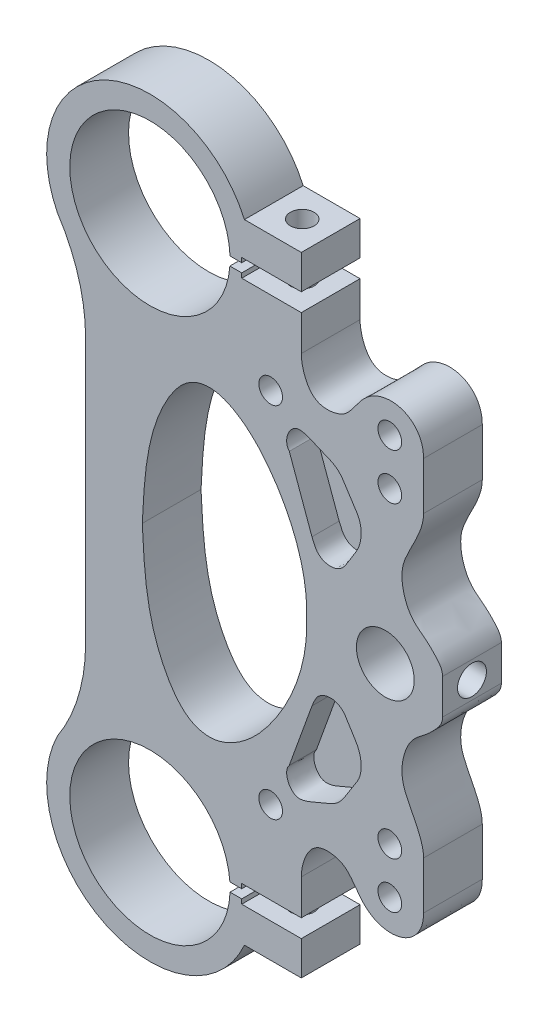
SolidWorks part; units mm, degrees
ref_plane "Piano frontale" through (0, 0, 0) normal (0, 0, 1) x (1, 0, 0)
ref_plane "Piano superiore" through (0, 0, 0) normal (0, 1, 0) x (1, 0, 0)
ref_plane "Piano destro" through (0, 0, 0) normal (1, 0, 0) x (0, 0, -1)
sketch "Schizzo1" plane through (0, 0, 0) normal (0, 0, 1) x (1, 0, 0)
  line L0 (44.652, 38.3399) -> (-8.3277, 38.3399) construction
  line L1 (10.783, 26.8988) -> (10.783, 49.781)
  line L2 (24.2823, 62.1538) -> (24.2823, 62.5538)
  line L3 (24.2823, 62.5538) -> (29.4323, 62.5538)
  line L4 (29.4323, 62.5538) -> (29.4323, 65.5038)
  line L5 (29.4323, 65.5038) -> (24.5149, 65.5038)
  line L6 (24.2823, 62.1538) -> (23.2712, 62.1538)
  line L7 (23.258, 61.3982) -> (24.2823, 61.3982)
  line L8 (24.2823, 61.3982) -> (24.2823, 60.9982)
  line L9 (24.2823, 60.9982) -> (29.4323, 60.9982)
  line L10 (29.4323, 60.9982) -> (29.4323, 57.9329)
  line L11 (40.0008, 55.359) -> (40.0008, 51.2344)
  line L12 (41.648, 39.8619) -> (41.648, 36.8178)
  line L13 (40.0008, 21.3208) -> (40.0008, 25.4454)
  line L14 (29.4323, 15.6815) -> (29.4323, 18.7468)
  line L15 (24.2823, 15.6815) -> (29.4323, 15.6815)
  line L16 (24.2823, 15.2815) -> (24.2823, 15.6815)
  line L17 (23.258, 15.2815) -> (24.2823, 15.2815)
  line L18 (24.2823, 14.5259) -> (23.2712, 14.5259)
  line L19 (29.4323, 11.1759) -> (24.5149, 11.1759)
  line L20 (29.4323, 14.1259) -> (29.4323, 11.1759)
  line L21 (24.2823, 14.1259) -> (29.4323, 14.1259)
  line L22 (24.2823, 14.5259) -> (24.2823, 14.1259)
  line L23 (28.3915, 50.0978) -> (30.3532, 44.6715) construction
  line L24 (28.3915, 26.5819) -> (30.3532, 32.0083) construction
  line L25 (37.083, 51.6399) -> (37.083, 55.6399) construction
  circle A0 centre (36.6966, 38.3399) radius 2.5
  circle A1 centre (16.3459, 61.8965) radius 6.93
  arc A2 (24.5149, 65.5038) -> (9.0355, 56.7679) centre (16.3459, 61.8965) ccw
  arc A3 (10.783, 49.781) -> (8.3437, 57.9329) centre (-4.0586, 49.781) ccw
  circle A4 centre (16.3459, 61.8965) radius 8.93 construction
  arc A5 (10.783, 26.8988) -> (8.3437, 18.7468) centre (-4.0586, 26.8988) cw
  arc A6 (24.5149, 11.1759) -> (9.0355, 19.9118) centre (16.3459, 14.7832) cw
  circle A7 centre (16.3459, 14.7832) radius 6.93
  circle A8 centre (26.783, 53.8399) radius 1.1499 construction
  circle A9 centre (37.083, 55.6399) radius 1.1192 construction
  circle A10 centre (37.083, 51.6399) radius 1.0752 construction
  circle A11 centre (26.783, 22.8399) radius 1.1499 construction
  circle A12 centre (37.083, 21.0399) radius 1.1192 construction
  circle A13 centre (37.083, 25.0399) radius 1.0752 construction
  spline S0 degree 3 poles (40.0008, 55.359) (40.0008, 55.8035) (39.8397, 56.7649) (38.7622, 58.0352) (36.9415, 58.4478) (35.0744, 57.7178) (34.1411, 56.3789) (33.2869, 55.2468) (32.1191, 54.8054) (30.8052, 54.8766) (29.7077, 56.046) (29.4323, 57.3454) (29.4323, 57.9329) knots 0 0 0 0 0.086235 0.18461 0.30636 0.425659 0.552279 0.62003 0.697314 0.787231 0.85642 1 1 1 1
  spline S1 degree 3 poles (40.0008, 51.2344) (40.0008, 50.771) (39.7217, 49.6561) (38.9038, 48.1195) (38.0379, 46.3694) (38.1748, 44.4393) (38.9027, 42.8192) (40.12, 41.9865) (41.0426, 41.1272) (41.648, 40.3961) (41.648, 39.8619) knots 0 0 0 0 0.103904 0.2667 0.404029 0.548278 0.701668 0.797389 0.884227 1 1 1 1
  spline S2 degree 3 poles (40.0008, 25.4454) (40.0008, 25.9087) (39.7217, 27.0237) (38.9038, 28.5602) (38.0379, 30.3104) (38.1748, 32.2404) (38.9027, 33.8605) (40.12, 34.6933) (41.0426, 35.5525) (41.648, 36.2836) (41.648, 36.8178) knots 0 0 0 0 0.103904 0.2667 0.404029 0.548278 0.701668 0.797389 0.884227 1 1 1 1
  spline S3 degree 3 poles (40.0008, 21.3208) (40.0008, 20.8762) (39.8397, 19.9149) (38.7622, 18.6446) (36.9415, 18.232) (35.0744, 18.9619) (34.1411, 20.3009) (33.2869, 21.4329) (32.1191, 21.8743) (30.8052, 21.8031) (29.7077, 20.6337) (29.4323, 19.3344) (29.4323, 18.7468) knots 0 0 0 0 0.086235 0.18461 0.30636 0.425659 0.552279 0.62003 0.697314 0.787231 0.85642 1 1 1 1
  spline S4 degree 3 poles (15.6826, 38.3399) (15.8621, 41.8407) (16.077, 46.4843) (19.436, 51.1792) (22.0032, 51.5591) (24.463, 50.5183) (27.0177, 47.7705) (29.3099, 43.5608) (29.9723, 40.1777) (29.8861, 38.3399) knots 0 0 0 0 0.321955 0.444159 0.483908 0.555795 0.683183 0.828712 1 1 1 1
  spline S5 degree 3 poles (15.6826, 38.3399) (15.8621, 34.839) (16.077, 30.1954) (19.436, 25.5005) (22.0032, 25.1207) (24.463, 26.1614) (27.0177, 28.9092) (29.3099, 33.119) (29.9723, 36.5021) (29.8861, 38.3399) knots 0 0 0 0 0.321955 0.444159 0.483908 0.555795 0.683183 0.828712 1 1 1 1
  spline S6 degree 3 poles (28.3915, 50.0978) (27.8594, 50.7048) (28.4692, 52.3186) (30.0286, 52.0526) (31.1131, 51.4818) (32.3557, 51.1014) (33.193, 50.1474) (33.7119, 49.1497) (34.5378, 48.0878) (34.6681, 46.8838) (34.3882, 45.7037) (33.6402, 44.7109) (33.0671, 43.5351) (32.0346, 43.17) (31.284, 43.3773) (30.8794, 43.6857) (30.6816, 43.8562) (30.3532, 44.6715) knots 0 0 0 0 0.13684 0.17515 0.257072 0.352961 0.390177 0.472943 0.54801 0.617627 0.673801 0.753613 0.832487 0.887817 0.933329 0.944548 1 1 1 1 construction
  spline S7 degree 3 poles (28.3915, 26.5819) (27.8594, 25.9749) (28.4692, 24.3611) (30.0286, 24.6271) (31.1131, 25.1979) (32.3557, 25.5784) (33.193, 26.5324) (33.7119, 27.53) (34.5378, 28.592) (34.6681, 29.7959) (34.3882, 30.9761) (33.6402, 31.9689) (33.0671, 33.1447) (32.0346, 33.5098) (31.284, 33.3025) (30.8794, 32.994) (30.6816, 32.8235) (30.3532, 32.0083) knots 0 0 0 0 0.13684 0.17515 0.257072 0.352961 0.390177 0.472943 0.54801 0.617627 0.673801 0.753613 0.832487 0.887817 0.933329 0.944548 1 1 1 1 construction
  point P72 (41.648, 38.3399)
  point P81 (10.783, 38.3399)
  dimension "D1" = 5
  dimension "D2" = 13.86
  dimension "D3" = 2.95
  dimension "D4" = 0.4
  dimension "D5" = 5.15
  dimension "D7" = 4
  dimension "D8" = 15.5
  dimension "D9" = 16
  dimension "D10" = 26.3
  dimension "D11" = 13.3
  dimension "D6" = 2
extrude "Estrusione-Estrusione1" add sketch "Schizzo1" along normal blind 5.08 contours S3 L13 S2 L12 S1 L11 S0 L10 L9 L8 L7 A1 L6 L2 L3 L4 L5 A2 A3 L1 A5 A6 L19 L20 L21 L22 L18 A7 L17 L16 L15 L14 S5 S4 A0
sketch "Schizzo2" plane through (0, 0, 5.08) normal (0, 0, 1) x (1, 0, 0)
  line L0 (28.3915, 50.0978) -> (30.3532, 44.6715) construction
  line L1 (28.3915, 26.5819) -> (30.3532, 32.0083) construction
  line L2 (28.3915, 50.0978) -> (30.3532, 44.6715)
  line L3 (28.3915, 26.5819) -> (30.3532, 32.0083)
  spline S0 degree 3 poles (1436.732, 2697.3918) (51.5713, -113.5731) (19.2159, 53.8971) (30.0286, 52.0526) (31.1131, 51.4818) (32.3557, 51.1014) (33.193, 50.1474) (33.7119, 49.1497) (34.5378, 48.0878) (34.6681, 46.8838) (34.3882, 45.7037) (33.6402, 44.7109) (33.0671, 43.5351) (32.0346, 43.17) (31.284, 43.3773) (27.8435, 46.0003) (32.4766, 46.1184) (-774.2479, 2934.6543) knots -1.525496 -1.525496 -1.525496 -1.525496 0.13684 0.17515 0.257072 0.352961 0.390177 0.472943 0.54801 0.617627 0.673801 0.753613 0.832487 0.887817 0.933329 0.944548 1.841826 1.841826 1.841826 1.841826 only from (28.3915, 50.0978) to (30.3532, 44.6715) construction
  spline S1 degree 3 poles (1436.732, -2620.712) (51.5713, 190.2528) (19.2159, 22.7827) (30.0286, 24.6271) (31.1131, 25.1979) (32.3557, 25.5784) (33.193, 26.5324) (33.7119, 27.53) (34.5378, 28.592) (34.6681, 29.7959) (34.3882, 30.9761) (33.6402, 31.9689) (33.0671, 33.1447) (32.0346, 33.5098) (31.284, 33.3025) (27.8435, 30.6795) (32.4766, 30.5613) (-774.2479, -2857.9746) knots -1.525496 -1.525496 -1.525496 -1.525496 0.13684 0.17515 0.257072 0.352961 0.390177 0.472943 0.54801 0.617627 0.673801 0.753613 0.832487 0.887817 0.933329 0.944548 1.841826 1.841826 1.841826 1.841826 only from (28.3915, 26.5819) to (30.3532, 32.0083) construction
  spline S2 degree 3 poles (28.3915, 50.0978) (27.8594, 50.7048) (28.4692, 52.3186) (30.0286, 52.0526) (31.1131, 51.4818) (32.3557, 51.1014) (33.193, 50.1474) (33.7119, 49.1497) (34.5378, 48.0878) (34.6681, 46.8838) (34.3882, 45.7037) (33.6402, 44.7109) (33.0671, 43.5351) (32.0346, 43.17) (31.284, 43.3773) (30.8794, 43.6857) (30.6816, 43.8562) (30.3532, 44.6715) knots 0 0 0 0 0.13684 0.17515 0.257072 0.352961 0.390177 0.472943 0.54801 0.617627 0.673801 0.753613 0.832487 0.887817 0.933329 0.944548 1 1 1 1
  spline S3 degree 3 poles (28.3915, 26.5819) (27.8594, 25.9749) (28.4692, 24.3611) (30.0286, 24.6271) (31.1131, 25.1979) (32.3557, 25.5784) (33.193, 26.5324) (33.7119, 27.53) (34.5378, 28.592) (34.6681, 29.7959) (34.3882, 30.9761) (33.6402, 31.9689) (33.0671, 33.1447) (32.0346, 33.5098) (31.284, 33.3025) (30.8794, 32.994) (30.6816, 32.8235) (30.3532, 32.0083) knots 0 0 0 0 0.13684 0.17515 0.257072 0.352961 0.390177 0.472943 0.54801 0.617627 0.673801 0.753613 0.832487 0.887817 0.933329 0.944548 1 1 1 1
extrude "Taglio-Estrusione1" cut sketch "Schizzo2" against normal blind 2.35
hole_wizard "Foro filettato M2.5x0.45-1" positions "Schizzo4" profile "Schizzo3" tap size "M2.5x0.45" standard "Ansi Metric" end condition through all
sketch "Schizzo4" plane through (0, 0, 5.08) normal (0, 0, 1) x (1, 0, 0)
  point P0 (37.083, 25.0399)
  point P3 (37.083, 21.0399)
  point P6 (26.783, 22.8399)
  point P9 (26.783, 53.8399)
  point P12 (37.083, 55.6399)
  point P15 (37.083, 51.6399)
sketch "Schizzo3" plane through (37.083, 25.0399, 5.08) normal (1, 0, 0) x (0, -1, 0)
  line L0 (0, 0) -> (0, 5.08)
  line L1 (0, 5.08) -> (1.025, 5.08)
  line L2 (1.025, 5.08) -> (1.025, 0)
  line L5 (1.025, 0) -> (0, 0)
  line L11 (0, -6.35) -> (0, 107.95) construction
  dimension "Thread Major Dia." = 2.05
  dimension "Thru Tap Drill Depth" = 5.08
hole_wizard "Foro filettato M3x0.5-1" positions "Schizzo6" profile "Schizzo5" tap size "M3x0.5" standard "Ansi Metric"
sketch "Schizzo6" plane through (41.648, 0, 0) normal (1, 0, 0) x (0, 0, -1)
  line L0 (-5.08, 39.8619) -> (0, 36.8178) construction
  point P0 (-2.54, 38.3399)
  point P15 (-2.54, 38.3399)
sketch "Schizzo5" plane through (41.648, 38.3399, 2.54) normal (0, 1, 0) x (0, 0, -1)
  line L0 (0, 0) -> (0, 2.4514)
  line L1 (0, 2.4514) -> (1.25, 2.4514)
  line L2 (1.25, 2.4514) -> (1.25, 0)
  line L5 (1.25, 0) -> (0, 0)
  line L11 (0, -6.35) -> (0, 107.95) construction
  dimension "Thread Major Dia." = 2.5
  dimension "Thru Tap Drill Depth" = 2.4514
hole_wizard "Foro filettato M2.5x0.45-2" positions "Schizzo8" profile "Schizzo7" tap size "M2.5x0.45" standard "Ansi Metric"
sketch "Schizzo8" plane through (0, 65.5038, 0) normal (0, 1, 0) x (1, 0, 0)
  line L0 (29.4323, 0) -> (24.5149, 0) construction
  line L1 (29.4323, -5.08) -> (29.4323, 0) construction
  point P0 (26.9736, -2.54)
  point P6 (26.9736, 0)
  point P10 (29.4323, -2.54)
sketch "Schizzo7" plane through (26.9736, 65.5038, 2.54) normal (1, 0, 0) x (0, 0, 1)
  line L0 (0, 0) -> (0, 10.6159)
  line L1 (0, 10.6159) -> (1.025, 10)
  line L2 (1.025, 10) -> (1.025, 0)
  line L5 (1.025, 0) -> (0, 0)
  line L10 (0, 10.6159) -> (-1.025, 10) construction
  line L11 (0, -6.35) -> (0, 107.95) construction
  dimension "Tap Drill Dia." = 2.05
  dimension "Tap Drill Depth" = 10
  dimension "Drill Angle" = 118
ref_plane "Piano1" through (0, 38.3399, 0) normal (0, 1, 0) x (1, 0, 0)
mirror "Specchia1" about plane through (0, 38.3399, 0) normal (0, 1, 0) of "Foro filettato M2.5x0.45-2"
